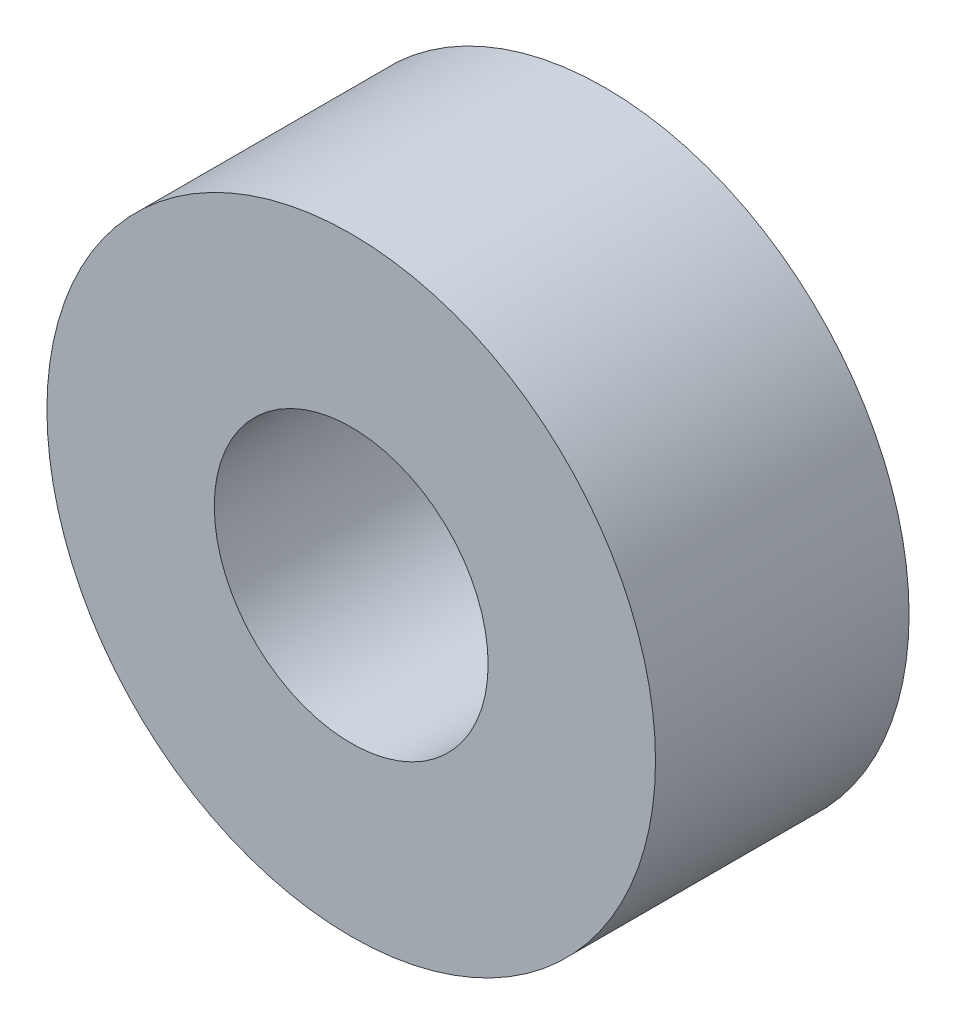
SolidWorks part; units mm, degrees
ref_plane "Front Plane" through (0, 0, 0) normal (0, 0, 1) x (1, 0, 0)
ref_plane "Top Plane" through (0, 0, 0) normal (0, 1, 0) x (1, 0, 0)
ref_plane "Right Plane" through (0, 0, 0) normal (1, 0, 0) x (0, 0, -1)
sketch "Sketch1" plane through (0, 0, 0) normal (0, 0, 1) x (1, 0, 0)
  circle A0 centre (0, 0) radius 3
  circle A1 centre (0, 0) radius 1.35
  dimension "D1" = 6
  dimension "D2" = 2.7
extrude "Boss-Extrude1" add sketch "Sketch1" along normal blind 2.5
